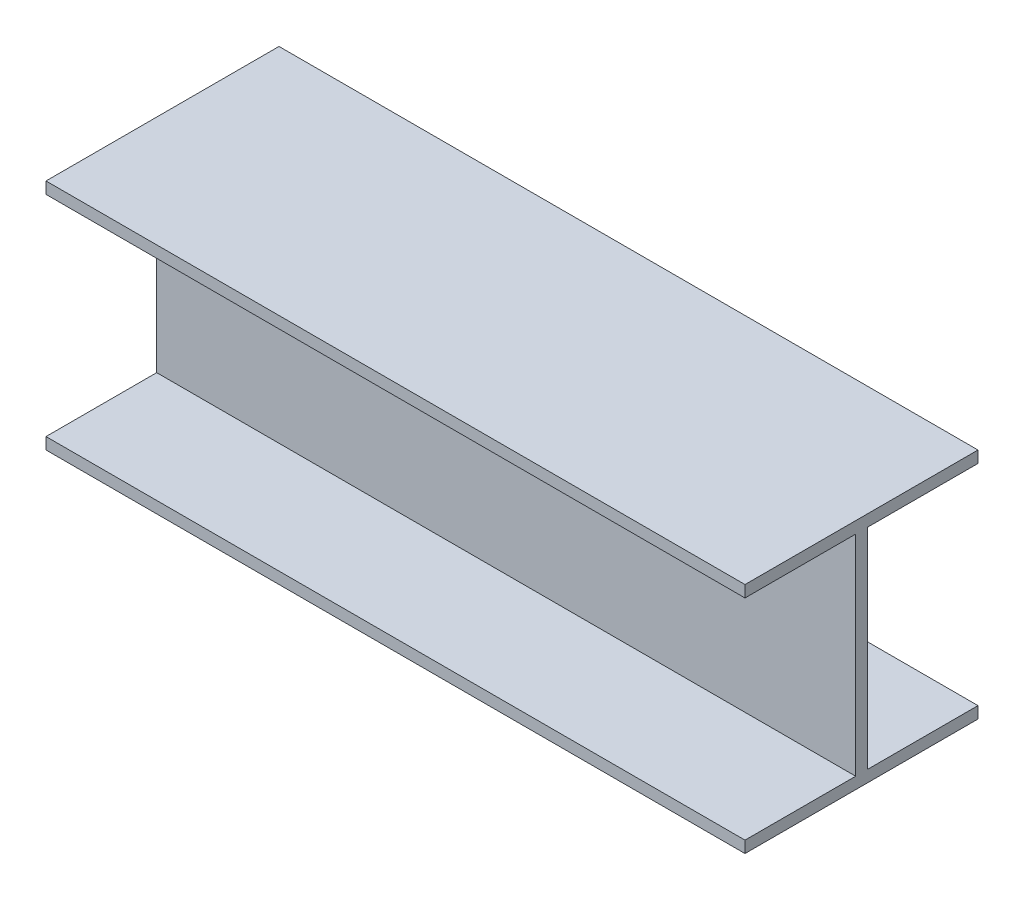
SolidWorks part; units mm, degrees
ref_plane "Piano frontale" through (0, 0, 0) normal (0, 0, 1) x (1, 0, 0)
ref_plane "Piano superiore" through (0, 0, 0) normal (0, 1, 0) x (1, 0, 0)
ref_plane "Piano destro" through (0, 0, 0) normal (1, 0, 0) x (0, 0, -1)
sketch "Sketch1" plane through (0, 0, 0) normal (1, 0, 0) x (0, 0, -1)
  line L0 (0, -100) -> (0, 100) construction
  line L1 (100, 100) -> (-100, 100)
  line L2 (-100, 100) -> (-100, 90)
  line L3 (-100, 90) -> (-5, 90)
  line L4 (-5, 90) -> (-5, -90)
  line L5 (-5, -90) -> (-100, -90)
  line L6 (-100, -90) -> (-100, -100)
  line L7 (-100, -100) -> (100, -100)
  line L8 (100, -90) -> (100, -100)
  line L9 (5, -90) -> (100, -90)
  line L10 (5, 90) -> (5, -90)
  line L11 (100, 90) -> (5, 90)
  line L12 (100, 100) -> (100, 90)
  point P4 (0, 0)
  dimension "D1" = 200
  dimension "D2" = 10
  dimension "D3" = 10
  dimension "D4" = 10
  dimension "D5" = 200
extrude "Boss-Extrude1" add sketch "Sketch1" along normal blind 600
